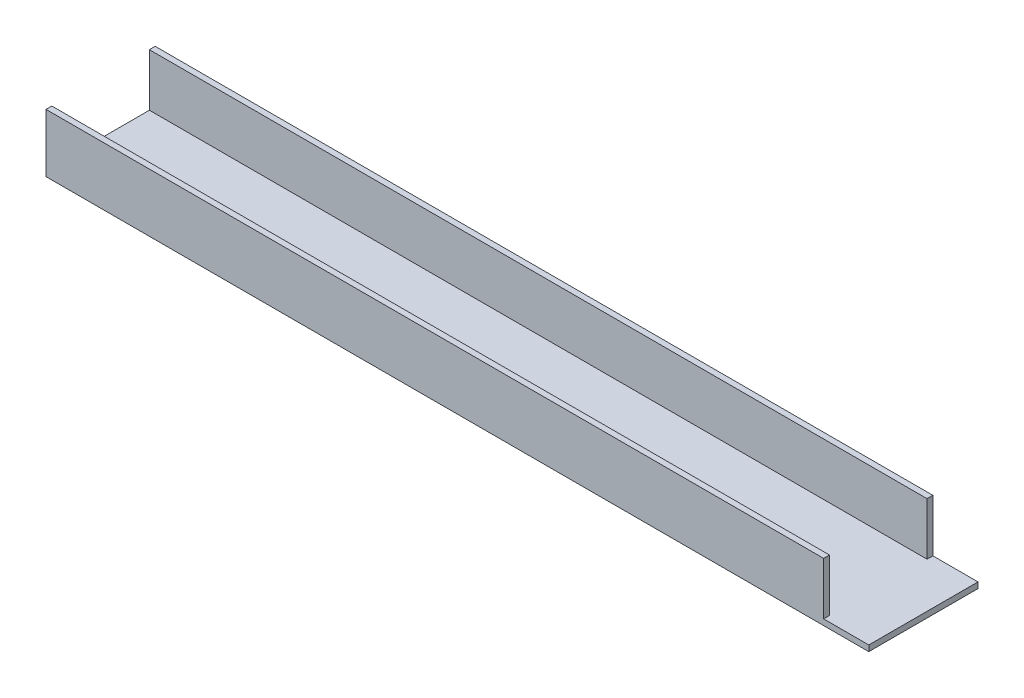
SolidWorks part; units mm, degrees
ref_plane "정면" through (0, 0, 0) normal (0, 0, 1) x (1, 0, 0)
ref_plane "윗면" through (0, 0, 0) normal (0, 1, 0) x (1, 0, 0)
ref_plane "우측면" through (0, 0, 0) normal (1, 0, 0) x (0, 0, -1)
sketch "스케치1" plane through (0, 0, 0) normal (0, 1, 0) x (1, 0, 0)
  line L1 (0, 0) -> (565, 0)
  line L2 (0, 0) -> (0, 75)
  line L3 (0, 75) -> (565, 75)
  line L4 (565, 0) -> (565, 75)
  dimension "D1" = 565
  dimension "D2" = 75
extrude "보스-돌출1" add sketch "스케치1" along normal blind 4
sketch "스케치2" plane through (0, 4, 0) normal (0, 1, 0) x (1, 0, 0)
  line L0 (565, 75) -> (0, 75) construction
  line L1 (0, 0) -> (534, 0)
  line L2 (0, 0) -> (0, 4)
  line L3 (0, 4) -> (534, 4)
  line L4 (534, 0) -> (534, 4)
  line L5 (534, 75) -> (0, 75)
  line L6 (534, 75) -> (534, 71)
  line L7 (534, 71) -> (0, 71)
  line L8 (0, 75) -> (0, 71)
  line L9 (0, 75) -> (0, 0) construction
  dimension "D1" = 4
  dimension "D2" = 4
  dimension "D3" = 534
extrude "보스-돌출2" add sketch "스케치2" along normal blind 36
